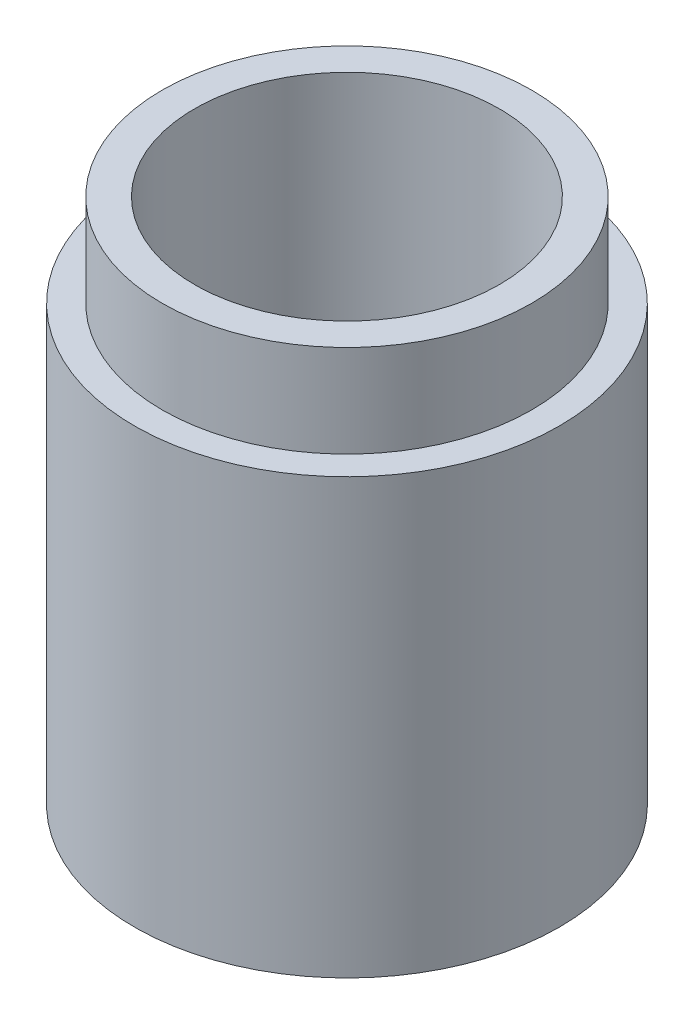
SolidWorks part; units mm, degrees
material "Brass"
ref_plane "Front Plane" through (0, 0, 0) normal (0, 0, 1) x (1, 0, 0)
ref_plane "Top Plane" through (0, 0, 0) normal (0, 1, 0) x (1, 0, 0)
ref_plane "Right Plane" through (0, 0, 0) normal (1, 0, 0) x (0, 0, -1)
sketch "Sketch1" plane through (0, 0, 0) normal (0, 0, 1) x (1, 0, 0)
  line L0 (0, -195.5213) -> (0, 9580.5453) construction
  line L1 (1.65, 0) -> (1.65, 5.7)
  line L2 (1.65, 5.7) -> (2, 5.7)
  line L3 (2, 5.7) -> (2, 4.7)
  line L4 (2, 4.7) -> (2.3, 4.7)
  line L5 (2.3, 4.7) -> (2.3, 0)
  line L6 (2.3, 0) -> (1.65, 0)
  point P5 (0, 0)
  dimension "D1" = 3.3
  dimension "D2" = 5.7
  dimension "D3" = 4.6
  dimension "D4" = 4
  dimension "D5" = 1
revolve "Revolve1" add sketch "Sketch1" angle 360 about L0
